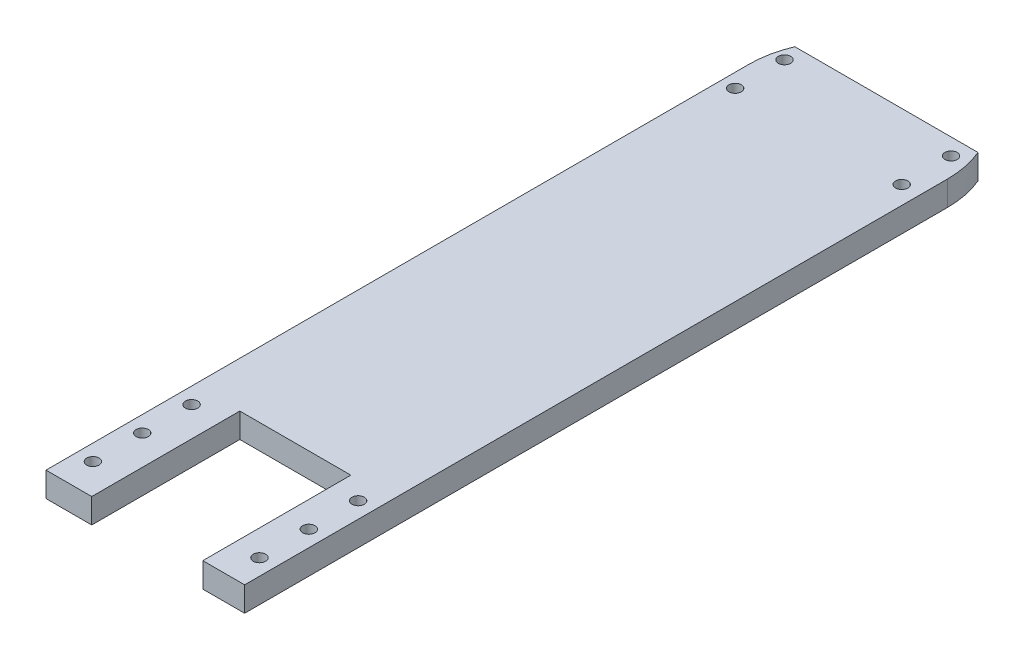
SolidWorks part; units mm, degrees
ref_plane "Plan de face" through (0, 0, 0) normal (0, 0, 1) x (1, 0, 0)
ref_plane "Plan de dessus" through (0, 0, 0) normal (0, 1, 0) x (1, 0, 0)
ref_plane "Plan de droite" through (0, 0, 0) normal (1, 0, 0) x (0, 0, -1)
sketch "Esquisse1" plane through (0, 0, 0) normal (0, 1, 0) x (1, 0, 0)
  line L0 (0, 0) -> (16.1, 0) construction
  line L1 (16.1, 0) -> (-16.1, 0) construction
  line L2 (0, -16.1) -> (0, 16.1) construction
  line L3 (0, 16.1) -> (-16.1, 16.1) construction
  line L4 (-16.1, 16.1) -> (-16.1, -113.9) construction
  line L5 (-16.1, 0) -> (-16.1, -113.9)
  line L6 (-16.1, -113.9) -> (16.1, -113.9)
  line L7 (16.1, -113.9) -> (16.1, 0)
  arc A0 (16.1, 0) -> (-16.1, 0) centre (0, 0) ccw
  dimension "D1" = 32.2
  dimension "D2" = 130
extrude "Boss.-Extru.1" add sketch "Esquisse1" along normal blind 4
sketch "Esquisse2" plane through (0, 4, 0) normal (0, 1, 0) x (1, 0, 0)
  line L0 (16.1, -113.9) -> (16.1, -108.9) construction
  line L1 (16.1, -113.9) -> (16.1, 0) construction
  line L2 (0, -113.9) -> (0, -108.9)
  line L3 (0, 16.1) -> (0, 0) construction
  line L4 (0, 0) -> (0, -30.9342) construction
  line L5 (0, 16.1) -> (0, 14.1) construction
  line L6 (-11, 0) -> (16.1, 0) construction
  line L7 (16.1, 0) -> (-16.1, 0) construction
  line L8 (0, -14.1) -> (11, -14.1) construction
  line L9 (0, -14.1) -> (-11, -14.1) construction
  line L10 (-11, -14.1) -> (-11, 0) construction
  line L11 (11, -14.1) -> (11, 0) construction
  line L12 (-16.1, -113.9) -> (16.1, -113.9) construction
  line L13 (13.5, -107.9) -> (13.5, -101.9)
  line L14 (-12.5, -108.9) -> (12.5, -108.9)
  line L15 (12.5, -108.9) -> (13.5, -108.9)
  line L16 (-12.5, -108.9) -> (-13.5, -108.9)
  line L17 (-13.5, -107.9) -> (-13.5, -101.9)
  line L18 (13.5, -101.9) -> (13.5, -100.9)
  line L19 (-13.5, -101.9) -> (-13.5, -100.9)
  line L20 (-13.5, -100.9) -> (-13.5, -99.9)
  line L21 (13.5, -100.9) -> (13.5, -99.9)
  line L22 (-13.5, -101.9) -> (13.5, -101.9)
  line L23 (-13.5, -99.9) -> (-13.5, -93.9)
  line L24 (13.5, -99.9) -> (13.5, -93.9)
  line L25 (13.5, -93.9) -> (13.5, -92.9)
  line L26 (0, 16.1) -> (0, 14.1) construction
  line L27 (0, 14.1) -> (0, 11.1) construction
  line L28 (0, 14.1) -> (0, 11.1) construction
  line L29 (0, 11.1) -> (0, 12.6) construction
  line L30 (-13.5, -93.9) -> (-13.5, -92.9)
  line L31 (13.1549, -5.4485) -> (13.1549, -4.4485)
  line L32 (-13.8451, -5.4485) -> (-13.8451, -4.4485)
  line L33 (-13.8451, -4.4485) -> (-13.8451, -3.4485)
  line L34 (13.1549, -4.4485) -> (13.1549, -3.4485)
  line L35 (-13.8451, -5.4485) -> (13.1549, -5.4485)
  line L36 (-13.8451, -3.4485) -> (-13.8451, 2.5515)
  line L37 (13.1549, -3.4485) -> (13.1549, 2.5515)
  line L38 (13.1549, 2.5515) -> (13.1549, 3.5515)
  line L39 (-13.8451, 2.5515) -> (-13.8451, 3.5515)
  line L40 (-14.8451, 6.2316) -> (14.8451, 6.2316)
  line L41 (14.8451, 6.2316) -> (14.8451, 23.6647)
  line L42 (14.8451, 23.6647) -> (-14.8451, 23.6647)
  line L43 (-14.8451, 23.6647) -> (-14.8451, 6.2316)
  arc A0 (16.1, 0) -> (-16.1, 0) centre (0, 0) ccw construction
  circle A15 centre (-13.5, -108.9) radius 1
  circle A16 centre (13.5, -108.9) radius 1
  circle A17 centre (-13.5, -100.9) radius 1
  circle A18 centre (13.5, -100.9) radius 1
  circle A19 centre (-13.5, -92.9) radius 1
  circle A20 centre (13.5, -92.9) radius 1
  circle A21 centre (-13.8451, -4.4485) radius 1
  circle A22 centre (13.1549, -4.4485) radius 1
  circle A23 centre (-13.8451, 3.5515) radius 1
  circle A24 centre (13.1549, 3.5515) radius 1
  point P36 (0, -108.9)
  dimension "D4" = 2
  dimension "D5" = 1
  dimension "D8" = 1
  dimension "D10" = 6
  dimension "D1" = 5
  dimension "D2" = 25
  dimension "D3" = 3
  dimension "D6" = 11
  dimension "D7" = 11
  dimension "D9" = 6
  dimension "D11" = 6
  dimension "D12" = 6
  dimension "D13" = 6
extrude "Enlèv. mat.-Extru.1" cut sketch "Esquisse2" against normal blind 4
sketch "Esquisse4" plane through (0, 4, 0) normal (0, 1, 0) x (1, 0, 0)
  line L0 (-8.684, -113.9) -> (9.316, -113.9)
  line L1 (-16.1, -113.9) -> (16.1, -113.9) construction
  line L2 (-8.684, -113.9) -> (-8.684, -89.9)
  line L3 (-8.684, -89.9) -> (9.316, -89.9)
  line L4 (9.316, -89.9) -> (9.316, -113.9)
  point P5 (0.316, -113.9)
extrude "Enlèv. mat.-Extru.2" cut sketch "Esquisse4" against normal blind 10 contours L4 L0 L2 L3
